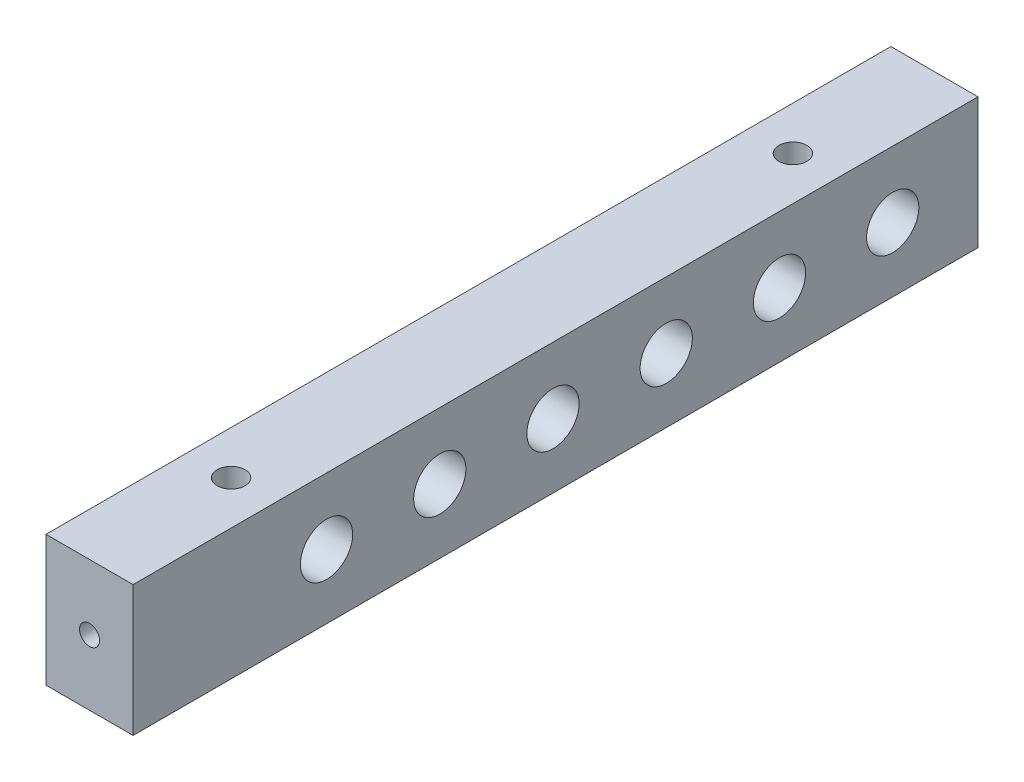
SolidWorks part; units mm, degrees
ref_plane "Front" through (0, 0, 0) normal (0, 0, 1) x (1, 0, 0)
ref_plane "Top" through (0, 0, 0) normal (0, 1, 0) x (1, 0, 0)
ref_plane "Right" through (0, 0, 0) normal (1, 0, 0) x (0, 0, -1)
sketch "Szkic1" plane through (0, 0, 0) normal (0, 0, 1) x (1, 0, 0)
  line L1 (0.3488, 8.2267) -> (10.3488, 8.2267)
  line L2 (0.3488, 8.2267) -> (0.3488, -6.7733)
  line L3 (0.3488, -6.7733) -> (10.3488, -6.7733)
  line L4 (10.3488, 8.2267) -> (10.3488, -6.7733)
  dimension "D1" = 10
  dimension "D2" = 15
extrude "Dodanie-wyciągnięcie1" add sketch "Szkic1" along normal blind 50
sketch "Szkic2" plane through (0, 0, 0) normal (0, 0, -1) x (-1, 0, 0)
  line L1 (-10.3488, 8.2267) -> (-0.3488, 8.2267)
  line L2 (-10.3488, 8.2267) -> (-10.3488, -6.7733)
  line L3 (-10.3488, -6.7733) -> (-0.3488, -6.7733)
  line L4 (-0.3488, 8.2267) -> (-0.3488, -6.7733)
extrude "Dodanie-wyciągnięcie2" add sketch "Szkic2" along normal up to surface (47 mm away)
ref_plane "Płaszczyzna1" through (5.3488, 0, 0) normal (-1, 0, 0) x (0, 0, 1)
sketch "Szkic3" plane through (0, 8.2267, 0) normal (0, 1, 0) x (1, 0, 0)
  circle A0 centre (5.3488, 30.75) radius 1.6
  circle A1 centre (5.3488, -33.75) radius 1.6
extrude "Wytnij-wyciągnięcie1" cut sketch "Szkic3" against normal through all
sketch "Szkic4" plane through (0, -6.7733, 0) normal (0, -1, 0) x (1, 0, 0)
  circle A0 centre (5.3488, -30.75) radius 3
  circle A1 centre (5.3488, 33.75) radius 3
  dimension "D1" = 6
extrude "Wytnij-wyciągnięcie2" cut sketch "Szkic4" against normal blind 3
sketch "Szkic5" plane through (0, 0, 50) normal (0, 0, 1) x (1, 0, 0)
  line L0 (0.3488, 8.2267) -> (10.3488, -6.7733) construction
  line L1 (10.3488, -6.7733) -> (10.3488, 8.2267) construction
  line L2 (10.3488, 8.2267) -> (0.3488, -6.7733) construction
  circle A0 centre (5.3488, 0.7267) radius 1.15
extrude "Wytnij-wyciągnięcie3" cut sketch "Szkic5" against normal blind 10
sketch "Szkic7" plane through (5.3488, 0, 0) normal (-1, 0, 0) x (0, 0, 1)
  line L0 (-32.35, 8.2267) -> (-29.15, 8.2267) construction
  line L1 (32.15, 8.2267) -> (35.35, 8.2267) construction
  line L2 (50, 1.8767) -> (40, 1.8767) construction
  line L3 (50, 1.8767) -> (40, 1.8767) construction
  line L4 (50, -0.6187) -> (40, -0.6187) construction
  line L5 (50, 1.8767) -> (50, -0.6187) construction
  line L6 (50, 0.629) -> (5.5859, 0.629) construction
  line L7 (32.15, 8.2267) -> (32.15, -4.581) construction
  line L8 (-29.15, 8.2267) -> (-29.15, -10.1082) construction
  circle A0 centre (27.793, 0.629) radius 3
  circle A1 centre (14.793, 0.629) radius 3
  circle A2 centre (1.793, 0.629) radius 3
  circle A3 centre (-11.207, 0.629) radius 3
  circle A4 centre (-24.207, 0.629) radius 3
  circle A5 centre (-37.207, 0.629) radius 3
  dimension "D1" = 6
extrude "Wytnij-wyciągnięcie4" cut sketch "Szkic7" against normal through all and the other way through all
